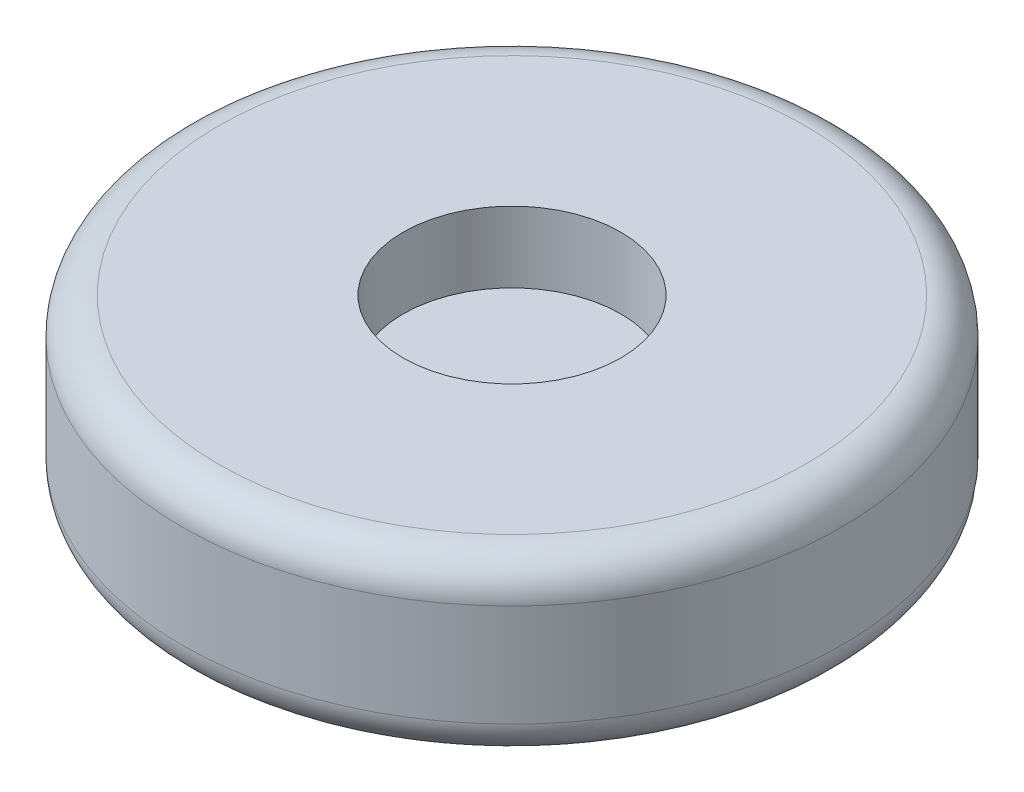
SolidWorks part; units mm, degrees
ref_plane "Front Plane" through (0, 0, 0) normal (0, 0, 1) x (1, 0, 0)
ref_plane "Top Plane" through (0, 0, 0) normal (0, 1, 0) x (1, 0, 0)
ref_plane "Right Plane" through (0, 0, 0) normal (1, 0, 0) x (0, 0, -1)
sketch "Sketch1" plane through (0, 0, 0) normal (1, 0, 0) x (0, 0, -1)
  line L0 (0, 41.2343) -> (0, -43.1301) construction
  line L6 (0, -12.118) -> (0, -15.348)
  line L7 (0, -15.348) -> (-16.15, -15.348)
  line L8 (-18.15, -13.348) -> (-18.15, -7.718)
  line L10 (-16.15, -5.718) -> (-6, -5.718)
  line L11 (-6, -5.718) -> (-6, -9.618)
  line L12 (-6, -9.618) -> (-14.25, -9.618)
  line L13 (-14.25, -9.618) -> (-14.25, -12.118)
  line L14 (-14.25, -12.118) -> (0, -12.118)
  arc A4 (-18.15, -13.348) -> (-16.15, -15.348) centre (-16.15, -13.348) ccw
  arc A5 (-18.15, -7.718) -> (-16.15, -5.718) centre (-16.15, -7.718) cw
  dimension "D1" = 9.63
  dimension "D2" = 18.15
  dimension "D3" = 28.5
  dimension "D4" = 3.9
  dimension "D5" = 12
  dimension "D6" = 2.5
revolve "Revolve1" add sketch "Sketch1" angle 360 about L0
